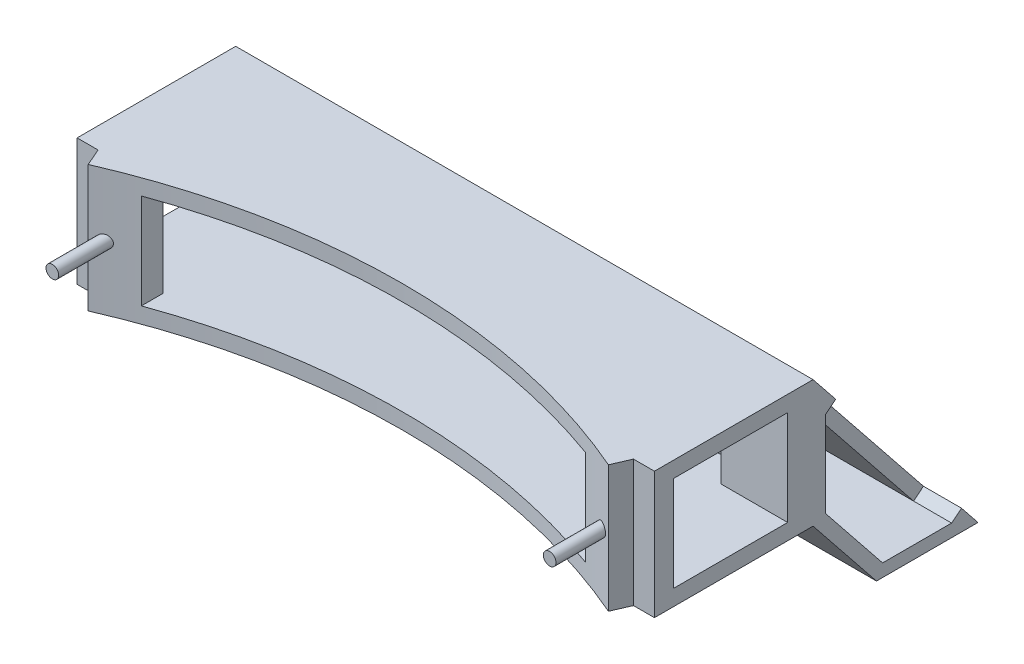
SolidWorks part; units mm, degrees
ref_plane "前视基准面" through (0, 0, 0) normal (0, 0, 1) x (1, 0, 0)
ref_plane "上视基准面" through (0, 0, 0) normal (0, 1, 0) x (1, 0, 0)
ref_plane "右视基准面" through (0, 0, 0) normal (1, 0, 0) x (0, 0, -1)
other "Configuration Table"
sketch "草图1" plane through (0, 0, 0) normal (0, 1, 0) x (1, 0, 0)
  line L0 (0, 0) -> (0, 103) construction
  line L3 (-41, 94.4881) -> (0, 103) construction
  line L4 (0, 103) -> (41, 94.4881) construction
  line L5 (0, 0) -> (-41, 94.4881) construction
  line L6 (-41, 94.4881) -> (-47.6088, 109.7187) construction
  line L7 (0, 0) -> (41, 94.4881) construction
  line L8 (41, 94.4881) -> (52.6521, 121.3413) construction
  line L9 (-42.1942, 97.2402) -> (-41, 94.4881)
  line L10 (42.1942, 97.2402) -> (41, 94.4881)
  circle A0 centre (0, 0) radius 103 construction
  arc A1 (-41, 94.4881) -> (41, 94.4881) centre (0, 0) cw
  circle A2 centre (0, 0) radius 106 construction
  arc A3 (-42.1942, 97.2402) -> (42.1942, 97.2402) centre (0, 0) cw
  dimension "D1" = 206
  dimension "D3" = 212
  dimension "D2" = 82
extrude "凸台-拉伸1" add sketch "草图1" along normal blind 20
sketch "草图2" plane through (0, 0, 0) normal (0, -1, 0) x (1, 0, 0)
  line L0 (-100, 0) -> (100, 0)
  line L1 (100, 0) -> (100, -1)
  line L2 (100, -1) -> (-100, -1)
  line L3 (-100, -1) -> (-100, 0)
  dimension "D1" = 200
  dimension "D2" = 100
  dimension "D3" = 1
extrude "凸台-拉伸2" add sketch "草图2" against normal blind 20 separate body
sketch "草图3" plane through (0, 0, -1) normal (0, 0, -1) x (-1, 0, 0)
  line L0 (42.1942, 20) -> (-42.1942, 20) construction
  line L1 (-42.1942, 20) -> (-42.1942, 0) construction
  line L2 (42.1942, 20) -> (42.1942, 0) construction
  circle A0 centre (-39.1942, 10) radius 1
  circle A1 centre (39.1942, 10) radius 1
  dimension "D3" = 2
  dimension "D4" = 2
  dimension "D1" = 10
  dimension "D2" = 10
  dimension "D5" = 3
  dimension "D6" = 3
extrude "凸台-拉伸3" add sketch "草图3" along normal blind 100
sketch "草图4" plane through (0, 0, -1) normal (0, 0, -1) x (-1, 0, 0)
  line L0 (42.1942, 20) -> (-42.1942, 20) construction
  line L1 (-35, 17.5) -> (35, 17.5)
  line L2 (-35, 17.5) -> (-35, 2.5)
  line L3 (-35, 2.5) -> (35, 2.5)
  line L4 (35, 17.5) -> (35, 2.5)
  line L7 (-41, 20) -> (-41, 0) construction
  line L8 (41, 20) -> (41, 0) construction
  dimension "D1" = 70
  dimension "D2" = 15
  dimension "D3" = 2.5
  dimension "D4" = 6
  dimension "D5" = 6
extrude "切除-拉伸1" cut sketch "草图4" along normal blind 150
sketch "草图5" plane through (0, 20, 0) normal (0, 1, 0) x (1, 0, 0)
  line L0 (-49.0579, 113.337) -> (-42.1942, 97.2402)
  line L1 (42.1942, 97.2402) -> (51.6281, 112.1896)
  arc A0 (-42.1942, 97.2402) -> (42.1942, 97.2402) centre (0, 0) cw
  arc A1 (42.1942, 97.2402) -> (-42.1942, 97.2402) centre (0, 0) ccw construction
  arc A2 (-49.0579, 113.337) -> (51.6281, 112.1896) centre (0, 0) cw
extrude "切除-拉伸2" cut sketch "草图5" against normal blind 150
sketch "草图6" plane through (0, 0, 0) normal (0, -1, 0) x (1, 0, 0)
  line L0 (41, -94.4881) -> (42.1942, -97.2402) construction
  line L1 (-42.1942, -97.2402) -> (-62.1942, -97.2402)
  line L2 (-62.1942, -97.2402) -> (-62.1942, -122.2402)
  line L3 (-62.1942, -122.2402) -> (62.1942, -122.2402)
  line L4 (62.1942, -122.2402) -> (62.1942, -97.2402)
  line L5 (62.1942, -97.2402) -> (42.1942, -97.2402)
  arc A0 (-42.1942, -97.2402) -> (42.1942, -97.2402) centre (0, 0) ccw
  dimension "D1" = 20
  dimension "D2" = 20
  dimension "D3" = 25
extrude "凸台-拉伸4" add sketch "草图6" against normal blind 20
sketch "草图7" plane through (0, 0, -122.2402) normal (0, 0, -1) x (-1, 0, 0)
  line L1 (-35, 17.5) -> (35, 17.5)
  line L2 (-35, 17.5) -> (-35, 2.5)
  line L3 (-35, 2.5) -> (35, 2.5)
  line L4 (35, 17.5) -> (35, 2.5)
extrude "切除-拉伸3" cut sketch "草图7" against normal blind 50
sketch "草图8" plane through (-62.1942, 0, 0) normal (-1, 0, 0) x (0, 0, 1)
  line L0 (-122.2402, 17.5) -> (-96.871, 17.5) construction
  line L1 (-118.2402, 17.5) -> (-100.2402, 17.5)
  line L2 (-118.2402, 17.5) -> (-118.2402, 2.5)
  line L3 (-118.2402, 2.5) -> (-100.2402, 2.5)
  line L4 (-100.2402, 17.5) -> (-100.2402, 2.5)
  line L5 (-122.2402, 2.5) -> (-96.871, 2.5) construction
  line L6 (-122.2402, 20) -> (-122.2402, 0) construction
  line L7 (-97.2402, 20) -> (-97.2402, 0) construction
  dimension "D1" = 4
  dimension "D2" = 3
extrude "切除-拉伸4" cut sketch "草图8" against normal blind 50
sketch "草图9" plane through (62.1942, 0, 0) normal (1, 0, 0) x (0, 0, -1)
  line L1 (100.2402, 17.5) -> (118.2402, 17.5)
  line L2 (100.2402, 17.5) -> (100.2402, 2.5)
  line L3 (100.2402, 2.5) -> (118.2402, 2.5)
  line L4 (118.2402, 17.5) -> (118.2402, 2.5)
extrude "切除-拉伸5" cut sketch "草图9" against normal blind 50
sketch "草图10" plane through (0, 20, 0) normal (0, 1, 0) x (1, 0, 0)
  line L5 (-124.3172, 87.029) -> (116.9307, 87.029)
  line L6 (-124.3172, 87.029) -> (-124.3172, -14.2923)
  line L7 (-124.3172, -14.2923) -> (116.9307, -14.2923)
  line L8 (116.9307, 87.029) -> (116.9307, -14.2923)
extrude "切除-拉伸6" cut sketch "草图10" against normal blind 50
sketch "草图11" plane through (0, 0, -122.2402) normal (0, 0, -1) x (-1, 0, 0)
  line L1 (62.1942, 0) -> (-62.1942, 0) construction
  line L2 (-62.1942, 32.5) -> (62.1942, 32.5)
  line L3 (-62.1942, 32.5) -> (-62.1942, -12.5)
  line L4 (-62.1942, -12.5) -> (62.1942, -12.5)
  line L5 (62.1942, 32.5) -> (62.1942, -12.5)
  line L6 (62.1942, 20) -> (-62.1942, 20) construction
  line L7 (62.1942, 20) -> (62.1942, 0) construction
  line L8 (-62.1942, 20) -> (-62.1942, 0) construction
  dimension "D1" = 45
  dimension "D2" = 12.5
  dimension "D3" = 12.5
  dimension "D4" = 0
  dimension "D5" = 0
extrude "凸台-拉伸5" add sketch "草图11" along normal blind 10
sketch "草图12" plane through (62.1942, 0, 0) normal (1, 0, 0) x (0, 0, -1)
  line L0 (122.2402, 20) -> (132.2402, 32.5)
  line L1 (132.2402, 32.5) -> (122.2402, 32.5)
  line L2 (122.2402, 32.5) -> (122.2402, 20)
  line L3 (122.2402, 0) -> (132.2402, -12.5)
  line L4 (132.2402, -12.5) -> (122.2402, -12.5) construction
  line L5 (132.2402, 32.5) -> (132.2402, -12.5) construction
  line L6 (132.2402, -12.5) -> (122.2402, -12.5)
  line L7 (122.2402, -12.5) -> (122.2402, 0)
extrude "切除-拉伸7" cut sketch "草图12" against normal blind 200
sketch "草图13" plane through (62.1942, 0, 0) normal (1, 0, 0) x (0, 0, -1)
  line L0 (122.2402, 0) -> (132.2402, -12.5)
  line L1 (132.2402, -12.5) -> (148.2402, -12.5)
  line L2 (148.2402, -12.5) -> (122.2402, 20)
  line L3 (122.2402, 20) -> (122.2402, 0)
extrude "凸台-拉伸6" add sketch "草图13" against normal blind 124.5 contours L2 L3 L0 L1
sketch "草图14" plane through (62.1942, 0, 0) normal (1, 0, 0) x (0, 0, -1)
  line L0 (122.2402, 20) -> (132.2402, 7.5)
  line L1 (132.2402, 7.5) -> (132.2402, 32.5)
  line L2 (132.2402, 32.5) -> (122.2402, 20)
extrude "切除-拉伸8" cut sketch "草图14" against normal blind 134.5
sketch "草图15" plane through (0, 20, 0) normal (0, 1, 0) x (1, 0, 0)
  line L0 (62.1942, 97.2402) -> (42.1942, 97.2402) construction
  line L1 (48.5, 97.2402) -> (62.1942, 97.2402)
  line L2 (48.5, 97.2402) -> (48.5, 148.2402)
  line L3 (48.5, 148.2402) -> (62.1942, 148.2402)
  line L4 (62.1942, 97.2402) -> (62.1942, 148.2402)
  line L5 (-62.3058, 148.2402) -> (62.1942, 148.2402) construction
  line L6 (-62.3058, 148.2402) -> (-48.5, 148.2402)
  line L7 (-62.3058, 148.2402) -> (-62.3058, 97.2402)
  line L8 (-62.3058, 97.2402) -> (-48.5, 97.2402)
  line L9 (-48.5, 148.2402) -> (-48.5, 97.2402)
  line L10 (-62.3058, 148.2402) -> (-62.3058, 122.2402) construction
  line L11 (-42.1942, 97.2402) -> (-62.1942, 97.2402) construction
  line L12 (-48.5, 97.2402) -> (-42.1942, 97.2402) construction
  line L13 (42.1942, 97.2402) -> (48.5, 97.2402) construction
  dimension "D1" = 97
extrude "切除-拉伸9" cut sketch "草图15" against normal blind 40
sketch "草图16" plane through (-48.5, 0, 0) normal (-1, 0, 0) x (0, 0, 1)
  line L0 (-122.2402, 0) -> (-122.2402, 20) construction
  line L1 (-124.2402, 14.2984) -> (-144.0789, -10.5)
  line L2 (-144.0789, -10.5) -> (-133.2014, -10.5)
  line L3 (-133.2014, -10.5) -> (-124.2402, 0.7016)
  line L4 (-124.2402, 0.7016) -> (-124.2402, 14.2984)
  line L5 (-122.2402, 0) -> (-132.2402, -12.5) construction
  line L6 (-148.2402, -12.5) -> (-132.2402, -12.5) construction
  line L7 (-122.2402, 20) -> (-148.2402, -12.5) construction
  dimension "D1" = 2
  dimension "D2" = 2
  dimension "D3" = 2
  dimension "D4" = 2
extrude "切除-拉伸10" cut sketch "草图16" against normal blind 120
sketch "草图17" plane through (0, 0, -124.2402) normal (0, 0, -1) x (-1, 0, 0)
  line L0 (35, 17.5) -> (-35, 17.5) construction
  line L1 (-33, 15.5) -> (33, 15.5)
  line L2 (-33, 15.5) -> (-33, 4.5)
  line L3 (-33, 4.5) -> (33, 4.5)
  line L4 (33, 15.5) -> (33, 4.5)
  line L5 (-35, 2.5) -> (35, 2.5) construction
  line L6 (35, 2.5) -> (35, 17.5) construction
  line L7 (-35, 17.5) -> (-35, 2.5) construction
  dimension "D1" = 2
  dimension "D2" = 2
  dimension "D3" = 2
  dimension "D4" = 2
extrude "切除-拉伸12" cut sketch "草图17" against normal blind 120 contours L4 L3 L2 L1
sketch "草图18" plane through (0, 20, 0) normal (0, 1, 0) x (1, 0, 0)
  line L0 (-42.1942, 97.2402) -> (-48.5, 97.2402) construction
  line L1 (-45.5, 97.2402) -> (-48.5, 97.2402)
  line L2 (-45.5, 97.2402) -> (-45.5, 148.2402)
  line L3 (-45.5, 148.2402) -> (-48.5, 148.2402)
  line L4 (-48.5, 97.2402) -> (-48.5, 148.2402)
  line L5 (48.5, 97.2402) -> (42.1942, 97.2402) construction
  line L6 (45.5, 97.2402) -> (48.5, 97.2402)
  line L7 (45.5, 97.2402) -> (45.5, 148.2402)
  line L8 (45.5, 148.2402) -> (48.5, 148.2402)
  line L9 (48.5, 97.2402) -> (48.5, 148.2402)
  line L10 (-45.5, 97.2402) -> (-42.1942, 97.2402) construction
  line L12 (42.1942, 97.2402) -> (45.5, 97.2402) construction
  dimension "D1" = 91
extrude "切除-拉伸13" cut sketch "草图18" against normal blind 120
sketch "草图20" plane through (0, 67.4342, -84.2928) normal (0, 0.6247, -0.7809) x (-1, 0, 0)
  line L1 (-45.5, -60.7455) -> (45.5, -60.7455)
  line L2 (-45.5, -60.7455) -> (-45.5, -102.3658)
  line L3 (-45.5, -102.3658) -> (45.5, -102.3658)
  line L4 (45.5, -60.7455) -> (45.5, -102.3658)
sketch "草图22" plane through (45.5, 0, 0) normal (1, 0, 0) x (0, 0, -1)
  line L0 (124.2402, 14.2984) -> (144.0789, -10.5)
  line L1 (124.2402, 14.2984) -> (128.1445, 17.4219)
  line L2 (144.0789, -10.5) -> (147.9833, -7.3765)
  line L3 (128.1445, 17.4219) -> (147.9833, -7.3765)
  dimension "D1" = 5
extrude "切除-拉伸14" cut sketch "草图22" against normal blind 6
